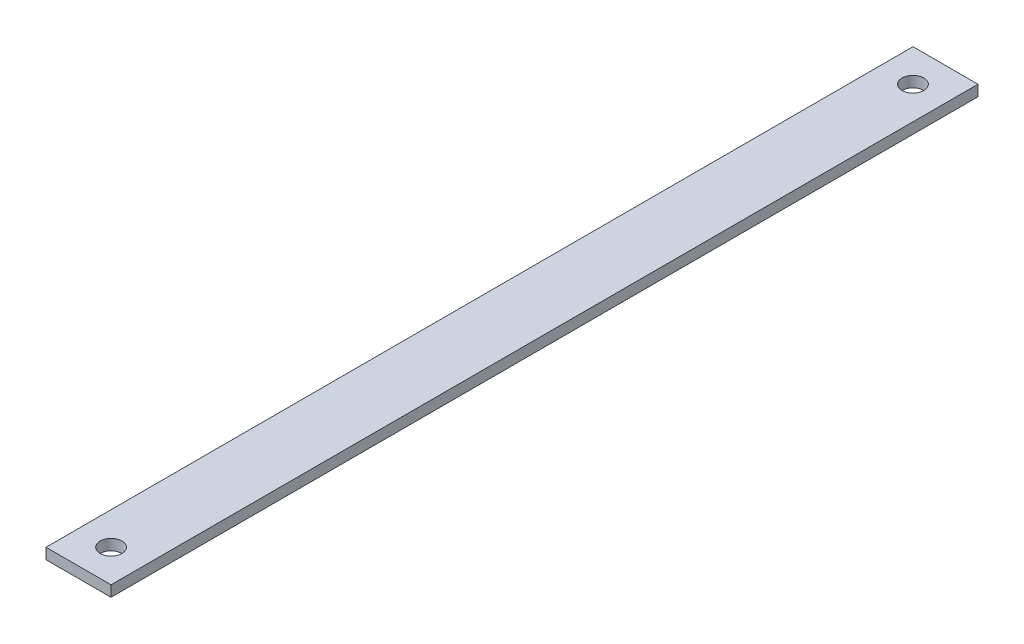
SolidWorks part; units mm, degrees
ref_plane "Front Plane" through (0, 0, 0) normal (0, 0, 1) x (1, 0, 0)
ref_plane "Top Plane" through (0, 0, 0) normal (0, 1, 0) x (1, 0, 0)
ref_plane "Right Plane" through (0, 0, 0) normal (1, 0, 0) x (0, 0, -1)
sketch "Sketch1" plane through (0, 0, 0) normal (0, 1, 0) x (1, 0, 0)
  line L0 (0, -117.475) -> (0, 117.475) construction
  line L1 (-9.525, -127) -> (9.525, -127)
  line L2 (-9.525, -127) -> (-9.525, 127)
  line L3 (-9.525, 127) -> (9.525, 127)
  line L4 (9.525, -127) -> (9.525, 127)
  line L5 (-9.525, -127) -> (9.525, 127) construction
  line L6 (-9.525, 127) -> (9.525, -127) construction
  circle A0 centre (0, 117.475) radius 3.1877
  circle A1 centre (0, -117.475) radius 3.1877
  point P0 (0, 0)
  point P9 (0, 0)
  dimension "D3" = 6.3754
  dimension "D1" = 254
  dimension "D2" = 19.05
  dimension "D4" = 9.525
extrude "Boss-Extrude1" add sketch "Sketch1" along normal blind 3.175
